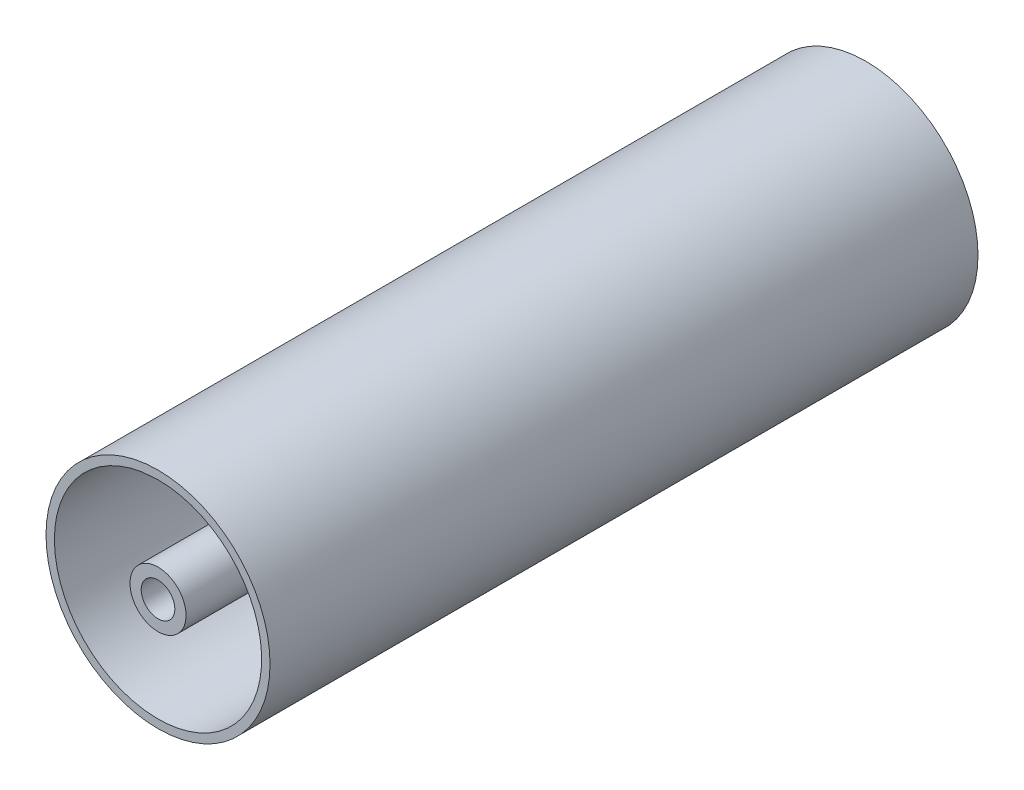
SolidWorks part; units mm, degrees
ref_plane "Спереди" through (0, 0, 0) normal (0, 0, 1) x (1, 0, 0)
ref_plane "Сверху" through (0, 0, 0) normal (0, 1, 0) x (1, 0, 0)
ref_plane "Справа" through (0, 0, 0) normal (1, 0, 0) x (0, 0, -1)
sketch "Эскиз2" plane through (0, 0, 0) normal (0, 0, 1) x (1, 0, 0)
  circle A0 centre (0, 0) radius 20
  circle A1 centre (0, 0) radius 18.5
  dimension "D1" = 40
  dimension "D2" = 37
extrude "Бобышка-Вытянуть1" add sketch "Эскиз2" along normal blind 126.4
sketch "Эскиз5" plane through (0, 0, 0) normal (0, 0, -1) x (-1, 0, 0)
  line L0 (0, 0) -> (0, 18.5) construction
  line L1 (0, 0) -> (2.9901, 18.2568) construction
  line L2 (0, 18.5) -> (0, 9.2195)
  line L3 (2.9901, 18.2568) -> (1.4901, 9.0983)
  circle A0 centre (0, 0) radius 18.5 construction
  arc A1 (0, 18.5) -> (2.9901, 18.2568) centre (0, 0) cw
  arc A2 (1.4901, 9.0983) -> (3.3687, 3.6948) centre (7.4112, 8.1286) ccw
  circle A3 centre (0, 0) radius 3
  arc A4 (-2.7273, 4.1907) -> (3.3687, 3.6948) centre (0, 0) ccw
  arc A5 (0, 9.2195) -> (-2.7273, 4.1907) centre (-6, 9.2195) cw
  point P16 (0, 5)
  dimension "D2" = 5
  dimension "D3" = 6
  dimension "D4" = 6
  dimension "D1" = 3
extrude "Бобышка-Вытянуть3" add sketch "Эскиз5" against normal through all
sketch "Sketch1" plane through (0, 0, 0) normal (0, 0, -1) x (-1, 0, 0)
  line L0 (0, 18.5) -> (2.9901, 18.2568)
  arc A2 (0, 18.5) -> (2.9901, 18.2568) centre (0, 0) ccw
  dimension "D1" = 18.5
extrude "Cut-Extrude1" cut sketch "Sketch1" against normal blind 59
sketch "Sketch2" plane through (0, 0, 126.4) normal (0, 0, 1) x (1, 0, 0)
  line L0 (0, 18.5) -> (-2.9901, 18.2568)
  arc A2 (0, 18.5) -> (-2.9901, 18.2568) centre (0, 0) cw
  dimension "D1" = 18.5
extrude "Cut-Extrude2" cut sketch "Sketch2" against normal blind 59
sketch "Sketch3" plane through (0, 0, 126.4) normal (0, 0, 1) x (1, 0, 0)
  circle A0 centre (0, 0) radius 5
  circle A1 centre (0, 0) radius 3
  dimension "D1" = 10
  dimension "D2" = 6
extrude "Boss-Extrude1" add sketch "Sketch3" against normal offset from surface (58.6 mm away) 0.4 separate body up to face at (-0.7247, 8.9083, 67.4)
